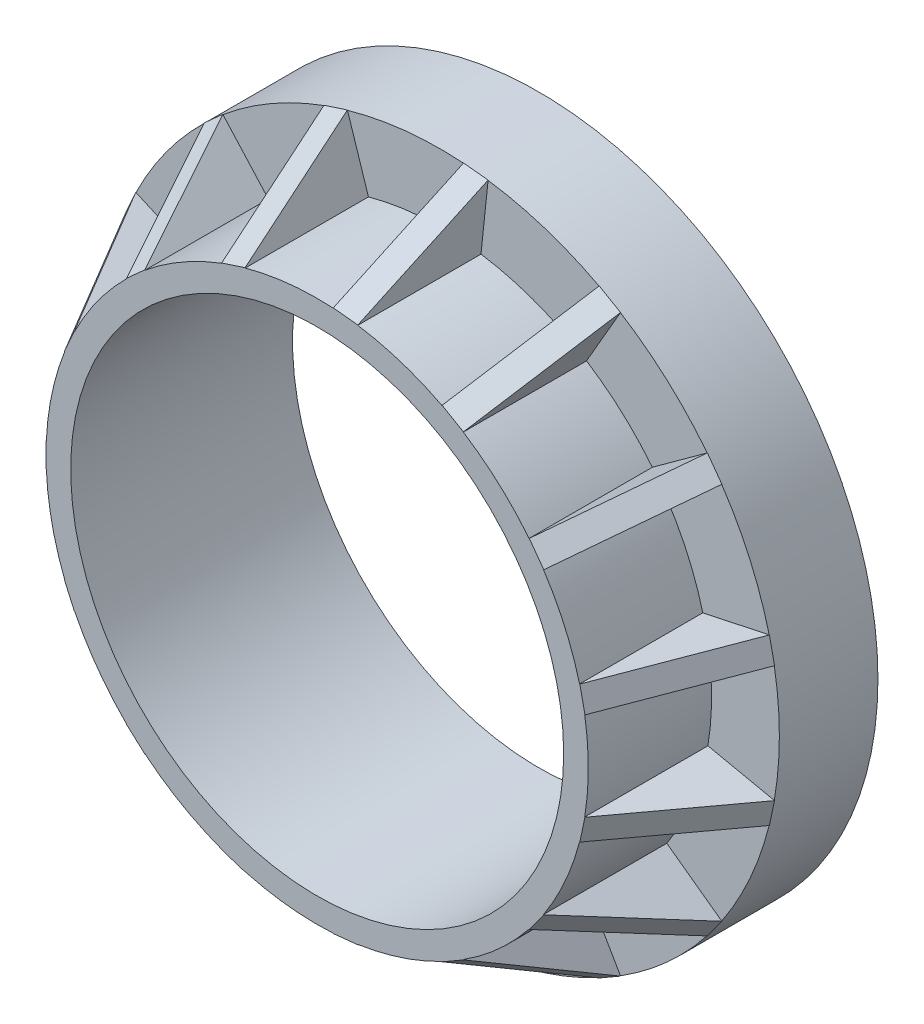
SolidWorks part; units mm, degrees
ref_plane "Front Plane" through (0, 0, 0) normal (0, 0, 1) x (1, 0, 0)
ref_plane "Top Plane" through (0, 0, 0) normal (0, 1, 0) x (1, 0, 0)
ref_plane "Right Plane" through (0, 0, 0) normal (1, 0, 0) x (0, 0, -1)
sketch "Sketch1" plane through (0, 0, 0) normal (0, 0, 1) x (1, 0, 0)
  circle A0 centre (0, 0) radius 27.5
  circle A1 centre (0, 0) radius 20
  dimension "D1" = 40
  dimension "D2" = 55
extrude "Boss-Extrude1" add sketch "Sketch1" along normal blind 8
sketch "Sketch2" plane through (0, 0, 8) normal (0, 0, 1) x (1, 0, 0)
  circle A0 centre (0, 0) radius 20 construction
  circle A1 centre (0, 0) radius 20
  circle A2 centre (0, 0) radius 22
  dimension "D1" = 2
extrude "Boss-Extrude2" add sketch "Sketch2" along normal blind 10
sketch "Sketch3" plane through (0, 0, 0) normal (0, 1, 0) x (1, 0, 0)
  line L0 (-22, -18) -> (-27.5, -8)
  line L1 (-27.5, -8) -> (-22, -8)
  line L3 (-22, -8) -> (22, -8) construction
  line L4 (-22, -18) -> (-20.5, -18)
  line L6 (-22, -8) -> (-20.5, -8)
  line L7 (-20.5, -18) -> (-20.5, -8)
  point P116 (-20.6156, -13)
  dimension "D1" = 1.5
extrude "Boss-Extrude3" add sketch "Sketch3" along normal mid plane 2
pattern_circular "CirPattern1" count 15 over 360 about axis through (0, 0, 0) along (0, 0, 1) of "Boss-Extrude3"
